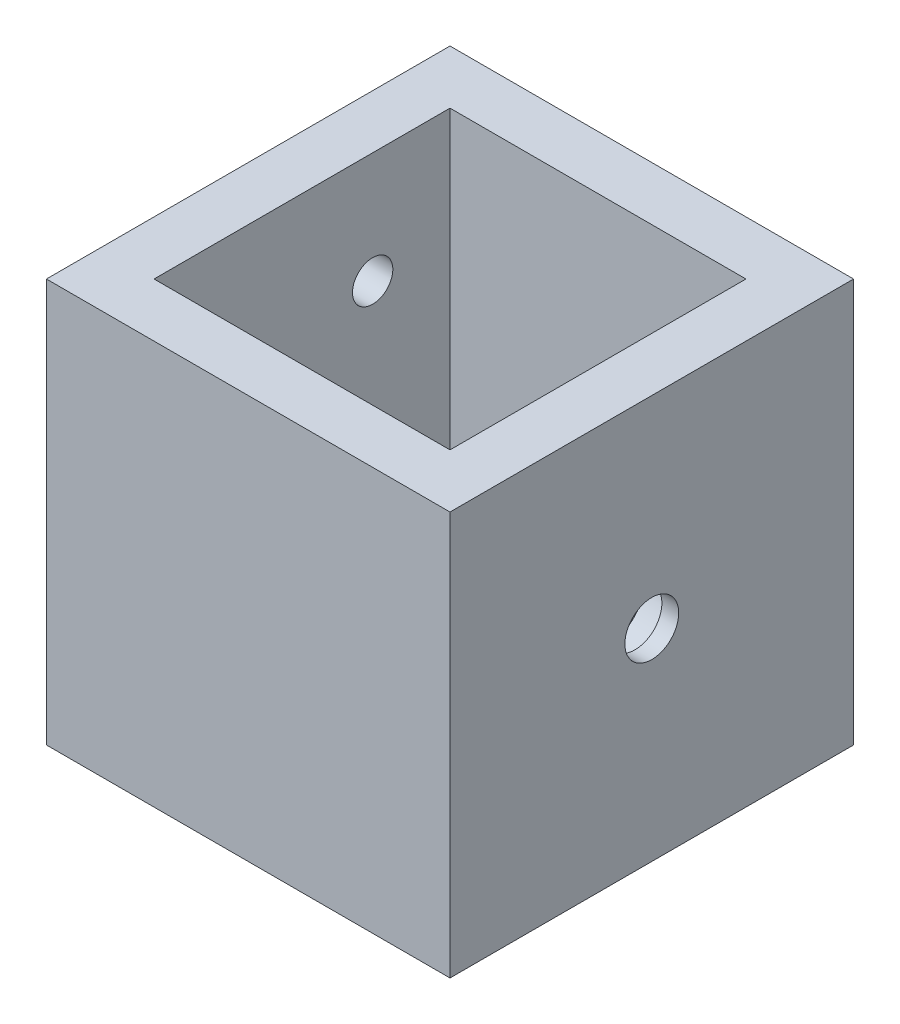
SolidWorks part; units mm, degrees
ref_plane "Front Plane" through (0, 0, 0) normal (0, 0, 1) x (1, 0, 0)
ref_plane "Top Plane" through (0, 0, 0) normal (0, 1, 0) x (1, 0, 0)
ref_plane "Right Plane" through (0, 0, 0) normal (1, 0, 0) x (0, 0, -1)
sketch "Sketch1" plane through (0, 0, 0) normal (0, 1, 0) x (1, 0, 0)
  line L1 (-30, 30) -> (30, 30)
  line L2 (-30, 30) -> (-30, -30)
  line L3 (-30, -30) -> (30, -30)
  line L4 (30, 30) -> (30, -30)
  line L5 (-30, 30) -> (30, -30) construction
  line L6 (-30, -30) -> (30, 30) construction
  point P0 (0, 0)
extrude "Boss-Extrude1" add sketch "Sketch1" along normal blind 60
sketch3d "3DSketch1"
  line L0 (-22, 60, -22) -> (-22, 60, 22)
  line L1 (-22, 60, 22) -> (22, 60, 22)
  line L2 (22, 60, 22) -> (22, 60, -22)
  line L3 (22, 60, -22) -> (-22, 60, -22)
  line L4 (-22, 60, -22) -> (-22, 60, 22)
  line L5 (-22, 60, 22) -> (22, 60, 22)
  line L6 (22, 60, 22) -> (22, 60, -22)
  line L7 (22, 60, -22) -> (-22, 60, -22)
  dimension "D1" = 8
extrude "Cut-Extrude1" cut sketch "3DSketch1" along direction (0, 1, 0) on the side against the normal blind 108
sketch "Sketch2" plane through (22, 0, 0) normal (-1, 0, 0) x (0, 0, 1)
  circle A0 centre (0, 30) radius 4
  dimension "D1" = 8
extrude "Cut-Extrude2" cut sketch "Sketch2" against normal blind 108
sketch "Sketch3" plane through (-30, 0, 0) normal (-1, 0, 0) x (0, 0, 1)
  line L1 (-10.5, 43.5) -> (10.5, 43.5)
  line L2 (-10.5, 43.5) -> (-10.5, 16.5)
  line L3 (-10.5, 16.5) -> (10.5, 16.5)
  line L4 (10.5, 43.5) -> (10.5, 16.5)
  line L5 (-10.5, 43.5) -> (10.5, 16.5) construction
  line L6 (-10.5, 16.5) -> (10.5, 43.5) construction
  circle A0 centre (-10.5, 43.5) radius 3
  circle A1 centre (10.5, 43.5) radius 3
  circle A2 centre (10.5, 16.5) radius 3
  circle A3 centre (-10.5, 16.5) radius 3
  point P0 (0, 30)
  dimension "D1" = 6
extrude "Cut-Extrude3" cut sketch "Sketch3" against normal blind 30 contours L1 A0 L2 | L2 A0 L1 | L4 A1 L1 | L1 A1 L4 | L3 A2 L4 | L4 A2 L3 | L2 A3 L3 | L3 A3 L2
sketch "Sketch4" plane through (22, 0, 0) normal (-1, 0, 0) x (0, 0, 1)
  circle A0 centre (0, 30) radius 7.5
extrude "Cut-Extrude4" cut sketch "Sketch4" against normal blind 5.5
